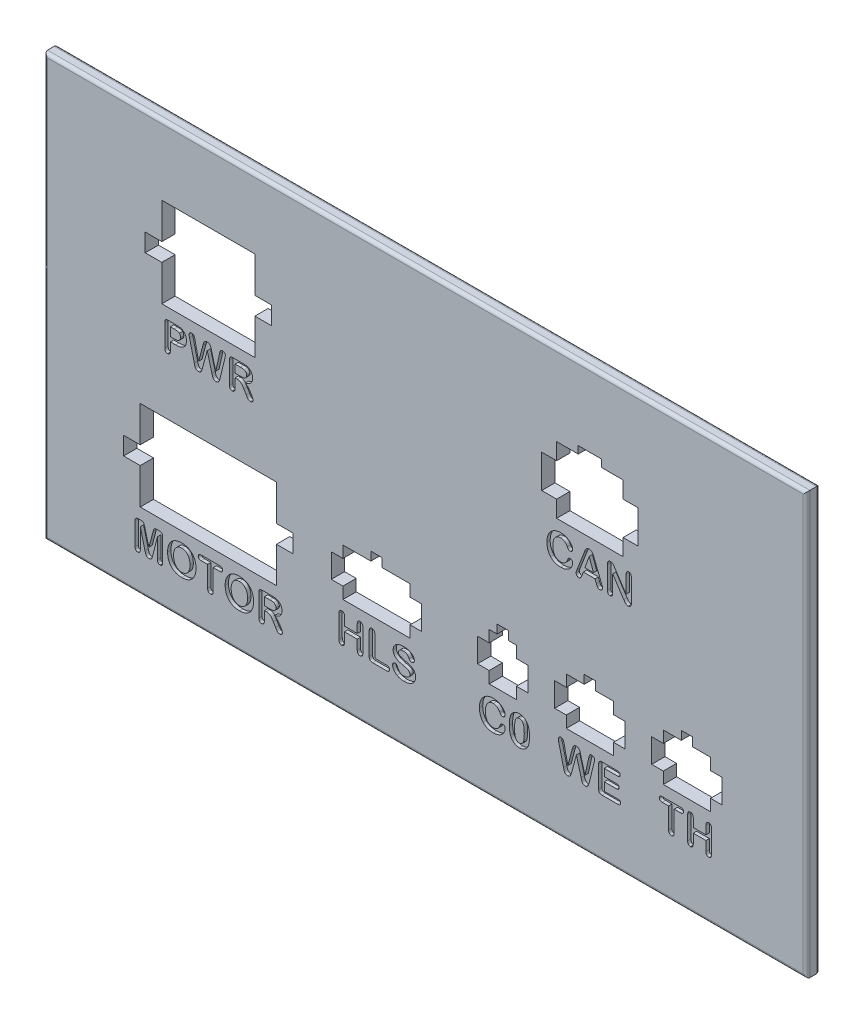
SolidWorks part; units mm, degrees
ref_plane "Front Plane" through (0, 0, 0) normal (0, 0, 1) x (1, 0, 0)
ref_plane "Top Plane" through (0, 0, 0) normal (0, 1, 0) x (1, 0, 0)
ref_plane "Right Plane" through (0, 0, 0) normal (1, 0, 0) x (0, 0, -1)
sketch "Sketch1" plane through (0, 0, 0) normal (0, 0, 1) x (1, 0, 0)
  line L1 (-52.9, -26.8) -> (52.9, -26.8)
  line L2 (-52.9, -26.8) -> (-52.9, 26.8)
  line L3 (-52.9, 26.8) -> (52.9, 26.8)
  line L4 (52.9, -26.8) -> (52.9, 26.8)
  line L5 (-52.9, -26.8) -> (52.9, 26.8) construction
  line L6 (-52.9, 26.8) -> (52.9, -26.8) construction
  point P0 (0, 0)
  dimension "D1" = 105.8
  dimension "D2" = 53.6
extrude "Boss-Extrude1" add sketch "Sketch1" along normal blind 2
sketch "Sketch2" plane through (0, 0, 0) normal (0, 0, 1) x (1, 0, 0)
  line L0 (9.6, -5) -> (13.7, -5)
  line L1 (-42.9, -1.8) -> (-22.4, -1.8)
  line L2 (-42.9, -1.8) -> (-42.9, -15.3)
  line L3 (-42.9, -15.3) -> (-22.4, -15.3)
  line L4 (-22.4, -1.8) -> (-22.4, -15.3)
  line L5 (19.75, 24.55) -> (29.75, 24.55)
  line L6 (19.75, 24.55) -> (19.75, 14.55)
  line L7 (19.75, 14.55) -> (29.75, 14.55)
  line L8 (29.75, 24.55) -> (29.75, 14.55)
  line L9 (35.8, -5) -> (42.9, -5)
  line L10 (35.8, -5) -> (35.8, -12.1)
  line L11 (35.8, -12.1) -> (42.9, -12.1)
  line L12 (42.9, -5) -> (42.9, -12.1)
  line L13 (9.6, -5) -> (9.6, -12.1)
  line L14 (9.6, -12.1) -> (13.7, -12.1)
  line L15 (13.7, -5) -> (13.7, -12.1)
  line L16 (-39.65, 26.3) -> (-25.65, 26.3)
  line L17 (-39.65, 26.3) -> (-39.65, 12.8)
  line L18 (-39.65, 12.8) -> (-25.65, 12.8)
  line L19 (-25.65, 26.3) -> (-25.65, 12.8)
  line L20 (21.2, -5) -> (28.3, -5)
  line L21 (21.2, -5) -> (21.2, -12.1)
  line L22 (21.2, -12.1) -> (28.3, -12.1)
  line L23 (28.3, -5) -> (28.3, -12.1)
  line L24 (-12.4, -5) -> (-2.3, -5)
  line L25 (-12.4, -5) -> (-12.4, -12.1)
  line L26 (-12.4, -12.1) -> (-2.3, -12.1)
  line L27 (-2.3, -5) -> (-2.3, -12.1)
  line L28 (-22.4, -8.55) -> (-12.4, -8.55) construction
  line L29 (13.7, -8.55) -> (21.2, -8.55) construction
  line L30 (28.3, -8.55) -> (35.8, -8.55) construction
  line L31 (-25.65, 19.55) -> (19.75, 19.55) construction
  line L32 (-32.65, -1.8) -> (-32.65, 12.8) construction
  line L33 (-2.3, -8.55) -> (9.6, -8.55) construction
  line L34 (24.75, -5) -> (24.75, 14.55) construction
  line L35 (-52.9, 26.8) -> (-52.9, -26.8) construction
  line L36 (52.9, -26.8) -> (52.9, 26.8) construction
  line L37 (52.9, 26.8) -> (-52.9, 26.8) construction
  line L38 (-52.9, -26.8) -> (52.9, -26.8) construction
  line L39 (-39.65, 12.8) -> (-25.65, 26.3) construction
  line L40 (-22.4, -1.8) -> (-42.9, -15.3) construction
  line L41 (-12.4, -12.1) -> (-2.3, -5) construction
  line L42 (9.6, -12.1) -> (13.7, -5) construction
  line L43 (21.2, -12.1) -> (28.3, -5) construction
  line L44 (35.8, -12.1) -> (42.9, -5) construction
  line L45 (19.75, 14.55) -> (29.75, 24.55) construction
  dimension "D1" = 20.5
  dimension "D2" = 13.5
  dimension "D3" = 10
  dimension "D4" = 10
  dimension "D5" = 7.1
  dimension "D6" = 7.1
  dimension "D7" = 4.1
  dimension "D8" = 7.1
  dimension "D9" = 14
  dimension "D10" = 13.5
  dimension "D11" = 7.1
  dimension "D12" = 7.1
  dimension "D13" = 10.1
  dimension "D14" = 7.1
  dimension "D15" = 7.5
  dimension "D16" = 10
  dimension "D17" = 10
  dimension "D18" = 0.5
  dimension "D19" = 11.5
  dimension "D20" = 10
extrude "Cut-Extrude2" cut sketch "Sketch2" along normal through all
sketch "Sketch4" plane through (0, 0, 2) normal (0, 0, 1) x (1, 0, 0)
  line L0 (-22.4, -1.8) -> (-42.9, -15.3) construction
  line L1 (-45.4, -7.2) -> (-19.9, -7.2)
  line L2 (-45.4, -7.2) -> (-45.4, -9.9)
  line L3 (-45.4, -9.9) -> (-19.9, -9.9)
  line L4 (-19.9, -7.2) -> (-19.9, -9.9)
  line L5 (-45.4, -7.2) -> (-19.9, -9.9) construction
  line L6 (-45.4, -9.9) -> (-19.9, -7.2) construction
  line L7 (-39.65, 12.8) -> (-25.65, 26.3) construction
  line L8 (-42.15, 20.9) -> (-23.15, 20.9)
  line L9 (-42.15, 20.9) -> (-42.15, 18.2)
  line L10 (-42.15, 18.2) -> (-23.15, 18.2)
  line L11 (-23.15, 20.9) -> (-23.15, 18.2)
  line L12 (-42.15, 20.9) -> (-23.15, 18.2) construction
  line L13 (-42.15, 18.2) -> (-23.15, 20.9) construction
  line L14 (19.75, 14.55) -> (29.75, 14.55) construction
  line L15 (23, 14.55) -> (26.5, 14.55)
  line L16 (23, 14.55) -> (23, 25.65)
  line L17 (23, 25.65) -> (26.5, 25.65)
  line L18 (26.5, 14.55) -> (26.5, 25.65)
  line L19 (24.75, 25.65) -> (24.75, 19.55) construction
  line L20 (19.75, 14.55) -> (29.75, 24.55) construction
  line L21 (9.6, -12.1) -> (13.7, -12.1) construction
  line L22 (17.5, 22.05) -> (32, 22.05)
  line L23 (17.5, 22.05) -> (17.5, 17.05)
  line L24 (17.5, 17.05) -> (32, 17.05)
  line L25 (32, 22.05) -> (32, 17.05)
  line L26 (17.5, 22.05) -> (32, 17.05) construction
  line L27 (17.5, 17.05) -> (32, 22.05) construction
  line L28 (10.8, -12.1) -> (12.5, -12.1)
  line L29 (10.8, -12.1) -> (10.8, -3.7)
  line L30 (10.8, -3.7) -> (12.5, -3.7)
  line L31 (12.5, -12.1) -> (12.5, -3.7)
  line L32 (21.2, -12.1) -> (28.3, -12.1) construction
  line L33 (23.9, -12.1) -> (25.6, -12.1)
  line L34 (23.9, -12.1) -> (23.9, -3.7)
  line L35 (23.9, -3.7) -> (25.6, -3.7)
  line L36 (25.6, -12.1) -> (25.6, -3.7)
  line L37 (35.8, -12.1) -> (42.9, -12.1) construction
  line L38 (38.5, -12.1) -> (40.2, -12.1)
  line L39 (38.5, -12.1) -> (38.5, -3.7)
  line L40 (38.5, -3.7) -> (40.2, -3.7)
  line L41 (40.2, -12.1) -> (40.2, -3.7)
  line L42 (11.65, -8.55) -> (11.65, -3.7) construction
  line L43 (9.6, -12.1) -> (13.7, -5) construction
  line L44 (-12.4, -12.1) -> (-2.3, -12.1) construction
  line L45 (21.2, -12.1) -> (28.3, -5) construction
  line L46 (24.75, -8.55) -> (24.75, -3.7) construction
  line L47 (-8.2, -12.1) -> (-6.5, -12.1)
  line L48 (35.8, -12.1) -> (42.9, -5) construction
  line L49 (39.35, -8.55) -> (39.35, -3.7) construction
  line L50 (-8.2, -12.1) -> (-8.2, -3.7)
  line L51 (-8.2, -3.7) -> (-6.5, -3.7)
  line L52 (-6.5, -12.1) -> (-6.5, -3.7)
  line L53 (-7.35, -8.55) -> (-7.35, -3.7) construction
  line L54 (-12.4, -12.1) -> (-2.3, -5) construction
  line L55 (-6.5, -3.7) -> (10.8, -3.7) construction
  line L56 (25.6, -3.7) -> (38.5, -3.7) construction
  line L57 (12.5, -3.7) -> (23.9, -3.7) construction
  line L58 (-0.55, -8.55) -> (-2.3, -8.55) construction
  line L59 (-14.15, -6.75) -> (-0.55, -6.75)
  line L60 (-14.15, -6.75) -> (-14.15, -10.35)
  line L61 (-14.15, -10.35) -> (-0.55, -10.35)
  line L62 (-0.55, -6.75) -> (-0.55, -10.35)
  line L63 (-14.15, -6.75) -> (-0.55, -10.35) construction
  line L64 (-14.15, -10.35) -> (-0.55, -6.75) construction
  line L65 (15.45, -6.75) -> (7.85, -6.75)
  line L66 (15.45, -6.75) -> (15.45, -10.35)
  line L67 (15.45, -10.35) -> (7.85, -10.35)
  line L68 (7.85, -6.75) -> (7.85, -10.35)
  line L69 (15.45, -6.75) -> (7.85, -10.35) construction
  line L70 (15.45, -10.35) -> (7.85, -6.75) construction
  line L71 (30.05, -6.75) -> (19.45, -6.75)
  line L72 (30.05, -6.75) -> (30.05, -10.35)
  line L73 (30.05, -10.35) -> (19.45, -10.35)
  line L74 (19.45, -6.75) -> (19.45, -10.35)
  line L75 (30.05, -6.75) -> (19.45, -10.35) construction
  line L76 (30.05, -10.35) -> (19.45, -6.75) construction
  line L77 (44.65, -6.75) -> (34.05, -6.75)
  line L78 (44.65, -6.75) -> (44.65, -10.35)
  line L79 (44.65, -10.35) -> (34.05, -10.35)
  line L80 (34.05, -6.75) -> (34.05, -10.35)
  line L81 (44.65, -6.75) -> (34.05, -10.35) construction
  line L82 (44.65, -10.35) -> (34.05, -6.75) construction
  line L83 (-2.3, -5) -> (-2.3, -12.1) construction
  line L84 (13.7, -8.55) -> (15.45, -8.55) construction
  line L85 (13.7, -5) -> (13.7, -12.1) construction
  line L86 (28.3, -8.55) -> (30.05, -8.55) construction
  line L87 (28.3, -5) -> (28.3, -12.1) construction
  line L88 (42.9, -8.55) -> (44.65, -8.55) construction
  line L89 (42.9, -5) -> (42.9, -12.1) construction
  line L90 (-2.3, -8.55) -> (9.6, -8.55) construction
  point P0 (-32.65, -8.55)
  point P7 (-32.65, 19.55)
  line M14 (-39.65, 12.8) -> (-39.65, 26.3)
  line M16 (-25.65, 26.3) -> (-25.65, 12.8)
  line M18 (-12.4, -12.1) -> (-12.4, -5)
  line M19 (-12.4, -5) -> (-2.3, -5)
  line M20 (-2.3, -5) -> (-2.3, -12.1)
  line M26 (-42.9, -15.3) -> (-42.9, -1.8)
  line M28 (-22.4, -1.8) -> (-22.4, -15.3)
  line M30 (21.2, -12.1) -> (21.2, -5)
  line M31 (21.2, -5) -> (28.3, -5)
  line M32 (28.3, -5) -> (28.3, -12.1)
  line M34 (9.6, -12.1) -> (9.6, -5)
  line M35 (9.6, -5) -> (13.7, -5)
  line M36 (13.7, -5) -> (13.7, -12.1)
  dimension "D1" = 25.5
  dimension "D2" = 2.7
  dimension "D3" = 2.7
  dimension "D4" = 19
  dimension "D5" = 3.5
  dimension "D6" = 11.1
  dimension "D7" = 14.5
  dimension "D8" = 5
  dimension "D9" = 8.4
  dimension "D10" = 1.7
  dimension "D11" = 10.6
  dimension "D12" = 3.6
extrude "Cut-Extrude5" cut sketch "Sketch4" against normal blind 10 contours L11 L8 L10 M16 | L9 L10 L8 M14 | L2 L3 L1 M26 | L4 L1 L3 M28 | L60 L61 L59 M18 | L62 L59 L61 M20 | L52 L51 L50 M19 | L31 L30 L29 M35 | L67 L66 L65 M36 | L65 L68 L67 M34 | L73 L72 L71 M32 | L71 L74 L73 M30 | L36 L35 L34 M31 | L77 L80 L79 L78 | L39 L40 L41 L38 | L16 L17 L18 L15 | L22 L25 L24 L23
sketch "Sketch5" plane through (0, 0, 0) normal (0, 0, 1) x (1, 0, 0)
  line L0 (-52.9, -26.8) -> (-57.9, -26.8)
  line L1 (-57.9, -26.8) -> (-57.9, 36.8)
  line L2 (-57.9, 36.8) -> (57.9, 36.8)
  line L3 (57.9, 36.8) -> (57.9, -26.8)
  line L4 (57.9, -26.8) -> (52.9, -26.8)
  line L6 (52.9, 26.8) -> (-52.9, 26.8)
  line L7 (52.9, 26.8) -> (52.9, -26.8)
  line L8 (52.9, -26.8) -> (-52.9, -26.8)
  line L9 (-52.9, 26.8) -> (-52.9, -26.8)
  line L10 (52.9, 26.8) -> (-52.9, -26.8) construction
  line L11 (52.9, -26.8) -> (-52.9, 26.8) construction
  point P6 (0, 0)
  dimension "D1" = 115.8
  dimension "D2" = 63.6
extrude "Boss-Extrude2" add sketch "Sketch5" along normal up to surface (2 mm away) contours L9 L6 L7 L4 L3 L2 L1 L0 up to face at (-32.65, -8.55, 2)
sketch "Sketch6" plane through (0, 0, 0) normal (0, 0, 1) x (1, 0, 0)
  line L0 (-57.35, 36.75) -> (57.35, -26.75) construction
  line L5 (-57.35, -26.75) -> (57.35, -26.75)
  line L6 (-57.35, -26.75) -> (-57.35, 36.75)
  line L7 (-57.35, 36.75) -> (57.35, 36.75)
  line L8 (57.35, -26.75) -> (57.35, 36.75)
  line L9 (-57.9, 36.8) -> (57.9, 36.8)
  line L10 (-57.9, 36.8) -> (-57.9, -26.8)
  line L11 (-57.9, -26.8) -> (57.9, -26.8)
  line L12 (57.9, 36.8) -> (57.9, -26.8)
  line L13 (57.9, 36.8) -> (-57.9, -26.8) construction
  point P4 (0, 5)
  dimension "D1" = 114.7
  dimension "D2" = 63.5
extrude "Cut-Extrude6" cut sketch "Sketch6" along normal through all
fillet "Fillet1" radius 0.5 8 edges at (0, 36.75, 0) (-57.35, 5, 0) (0, -26.75, 0) (57.35, 5, 0) (-57.35, 5, 2) (0, 36.75, 2) (0, -26.75, 2) (57.35, 5, 2)
sketch "Sketch7" plane through (0, 0, 2) normal (0, 0, 1) x (1, 0, 0)
  line L0 (7.85, -10.35) -> (15.45, -10.35) construction
  line L5 (7.85, -10.35) -> (7.85, -18.1) construction
  line L7 (-45.4, -9.9) -> (-19.9, -9.9) construction
  line L8 (-45.4, -9.9) -> (-45.4, -21.3) construction
  line L9 (-45.4, -21.3) -> (-19.9, -21.3) construction
  line L10 (-19.9, -9.9) -> (-19.9, -21.3) construction
  line L14 (-14.15, -10.35) -> (-0.55, -10.35) construction
  line L15 (-14.15, -10.35) -> (-14.15, -18.1) construction
  line L16 (-14.15, -18.1) -> (-0.55, -18.1) construction
  line L17 (-0.55, -10.35) -> (-0.55, -18.1) construction
  line L18 (7.85, -18.1) -> (15.45, -18.1) construction
  line L19 (15.45, -10.35) -> (15.45, -18.1) construction
  line L20 (19.45, -10.35) -> (30.05, -10.35) construction
  line L21 (19.45, -10.35) -> (19.45, -18.1) construction
  line L22 (19.45, -18.1) -> (30.05, -18.1) construction
  line L23 (30.05, -10.35) -> (30.05, -18.1) construction
  line L24 (34.05, -10.35) -> (44.65, -10.35) construction
  line L25 (34.05, -10.35) -> (34.05, -18.1) construction
  line L26 (34.05, -18.1) -> (44.65, -18.1) construction
  line L27 (44.65, -10.35) -> (44.65, -18.1) construction
  line L28 (-42.9, -15.3) -> (-22.4, -15.3) construction
  line L29 (-12.4, -12.1) -> (-2.3, -12.1) construction
  line L30 (17.5, 22.05) -> (32, 22.05) construction
  line L31 (9.6, -12.1) -> (13.7, -12.1) construction
  line L32 (17.5, 22.05) -> (17.5, 8.55) construction
  line L41 (17.5, 8.55) -> (32, 8.55) construction
  line L42 (32, 22.05) -> (32, 8.55) construction
  line L43 (-42.15, 20.9) -> (-23.15, 20.9) construction
  line L44 (-42.15, 20.9) -> (-42.15, 6.8) construction
  line L45 (-42.15, 6.8) -> (-23.15, 6.8) construction
  line L46 (-23.15, 20.9) -> (-23.15, 6.8) construction
  line L47 (-39.65, 12.8) -> (-25.65, 12.8) construction
  line L48 (19.75, 14.55) -> (29.75, 14.55) construction
  text T0 "PWR" font "Arial Rounded MT Bold" height 4.5
  text T1 "MOTOR" font "Arial Rounded MT Bold" height 4.5
  text T2 "CAN" font "Arial Rounded MT Bold" height 4.5
  text T3 "HLS" font "Arial Rounded MT Bold" height 4.5
  text T4 "C0" font "Arial Rounded MT Bold" height 4.5
  text T5 "WE" font "Arial Rounded MT Bold" height 4.5
  text T6 "TH" font "Arial Rounded MT Bold" height 4.5
  point P30 (17.9206, 23.2601)
  point P32 (16.398, 4.6378)
  point P38 (17.5, 20.55)
  point P40 (32, 20.55)
  point P50 (-48.6042, 4.2864)
  point P51 (-42.15, 19.4)
  point P53 (-23.15, 19.4)
  dimension "D1" = 6
  dimension "D2" = 6
  dimension "D3" = 6
  dimension "D4" = 6
  dimension "D5" = 6
extrude "Cut-Extrude7" cut sketch "Sketch7" against normal blind 0.5
